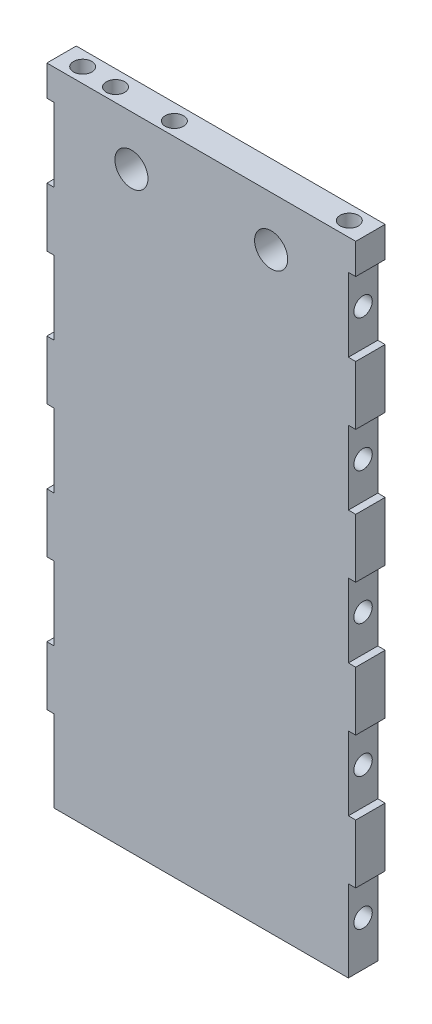
SolidWorks part; units mm, degrees
material "ABS"
ref_plane "前视基准面" through (0, 0, 0) normal (0, 0, 1) x (1, 0, 0)
ref_plane "上视基准面" through (0, 0, 0) normal (0, 1, 0) x (1, 0, 0)
ref_plane "右视基准面" through (0, 0, 0) normal (1, 0, 0) x (0, 0, -1)
sketch "草图1" plane through (0, 0, 0) normal (0, 0, 1) x (1, 0, 0)
  line L1 (42, -88.25) -> (-42, -88.25)
  line L2 (42, -88.25) -> (42, 88.25)
  line L3 (42, 88.25) -> (-42, 88.25)
  line L4 (-42, -88.25) -> (-42, 88.25)
  line L5 (42, -88.25) -> (-42, 88.25) construction
  line L6 (42, 88.25) -> (-42, -88.25) construction
  point P0 (0, 0)
  dimension "D1" = 176.5
  dimension "D2" = 84
extrude "凸台-拉伸1" add sketch "草图1" along normal mid plane 8
sketch "草图3" plane through (0, 0, -4) normal (0, 0, -1) x (-1, 0, 0)
  line L0 (42, 88.25) -> (42, -88.25) construction
  line L1 (32, 79.95) -> (-32, 79.95)
  line L2 (32, 79.95) -> (32, 86.25)
  line L3 (32, 86.25) -> (-32, 86.25)
  line L4 (-32, 79.95) -> (-32, 86.25)
  line L5 (-42, 88.25) -> (42, 88.25) construction
  line L6 (-42, -88.25) -> (-42, 88.25) construction
  dimension "D1" = 10
  dimension "D2" = 2
  dimension "D3" = 10
  dimension "D4" = 8.3
extrude "切除-拉伸1" [suppressed] cut sketch "草图3" against normal blind 10
ref_plane "基准面1" through (0, 91.25, 0) normal (0, 1, 0) x (1, 0, 0)
sketch "Sketch1" plane through (0, 0, 4) normal (0, 0, 1) x (1, 0, 0)
  line L0 (42, -88.25) -> (42, 88.25) construction
  line L1 (-42, 88.25) -> (42, 88.25)
  line L2 (-42, 88.25) -> (-42, 77.95)
  line L3 (-42, 77.95) -> (42, 77.95)
  line L4 (42, 88.25) -> (42, 77.95)
  dimension "D1" = 10.3
sketch "Sketch2" plane through (0, 0, 4) normal (0, 0, 1) x (1, 0, 0)
  line L0 (0, 0) -> (0, 60.2822) construction
  line L1 (-42, 77.95) -> (-40, 77.95)
  line L2 (-42, 77.95) -> (-42, 57.95)
  line L3 (-42, 57.95) -> (-40, 57.95)
  line L4 (-40, 77.95) -> (-40, 57.95)
  line L5 (-42, 41.95) -> (-40, 41.95)
  line L6 (-42, 41.95) -> (-42, 21.95)
  line L7 (-42, 21.95) -> (-40, 21.95)
  line L8 (-40, 41.95) -> (-40, 21.95)
  line L9 (-42, 5.95) -> (-40, 5.95)
  line L10 (-42, 5.95) -> (-42, -14.05)
  line L11 (-42, -14.05) -> (-40, -14.05)
  line L12 (-40, 5.95) -> (-40, -14.05)
  line L13 (-42, -30.05) -> (-40, -30.05)
  line L14 (-42, -30.05) -> (-42, -50.05)
  line L15 (-42, -50.05) -> (-40, -50.05)
  line L16 (-40, -30.05) -> (-40, -50.05)
  line L17 (-42, -66.05) -> (-40, -66.05)
  line L21 (-42, 77.95) -> (-42, 41.95) construction
  line L22 (42, 77.95) -> (42, 41.95) construction
  line L26 (42, -66.05) -> (40, -66.05)
  line L27 (40, -30.05) -> (40, -50.05)
  line L28 (42, -50.05) -> (40, -50.05)
  line L29 (42, -30.05) -> (42, -50.05)
  line L30 (42, -30.05) -> (40, -30.05)
  line L31 (40, 5.95) -> (40, -14.05)
  line L32 (42, -14.05) -> (40, -14.05)
  line L33 (42, 5.95) -> (42, -14.05)
  line L34 (42, 5.95) -> (40, 5.95)
  line L35 (40, 41.95) -> (40, 21.95)
  line L36 (42, 21.95) -> (40, 21.95)
  line L37 (42, 41.95) -> (42, 21.95)
  line L38 (42, 41.95) -> (40, 41.95)
  line L39 (40, 77.95) -> (40, 57.95)
  line L40 (42, 57.95) -> (40, 57.95)
  line L41 (42, 77.95) -> (42, 57.95)
  line L42 (42, 77.95) -> (40, 77.95)
  line L43 (-42, -86.05) -> (-40, -86.05) [skipped]
  line L44 (-40, -66.05) -> (-40, -86.05) [skipped]
  line L45 (-42, -66.05) -> (-42, -86.05) [skipped]
  line L46 (-42, -66.05) -> (-42, -88.25)
  line L47 (-42, -88.25) -> (-40, -88.25)
  line L48 (-42, -88.25) -> (42, -88.25) construction
  line L49 (-40, -88.25) -> (-40, -66.05)
  line L50 (40, -66.05) -> (40, -88.25)
  line L51 (40, -88.25) -> (42, -88.25)
  line L52 (42, -88.25) -> (42, -66.05)
  line L54 (-43, 86.25) -> (43, 86.25)
  line L55 (-43, 86.25) -> (-43, 88.25)
  line L56 (-43, 88.25) -> (43, 88.25)
  line L57 (43, 86.25) -> (43, 88.25)
  line L58 (-43, 86.25) -> (43, 88.25) construction
  line L59 (-43, 88.25) -> (43, 86.25) construction
  line L61 (-42, 88.25) -> (42, 88.25) construction
  line L62 (-42, 77.95) -> (42, 77.95) construction
  point P23 (0, 87.25)
  dimension "D1" = 20
  dimension "D2" = 2
  dimension "D4" = 36
  dimension "D5" = 86
  dimension "D6" = 2
  dimension "D3" = 5
extrude "Cut-Extrude1" cut sketch "Sketch2" against normal through all and the other way through all
sketch "Sketch3" plane through (40, 0, 0) normal (1, 0, 0) x (0, 0, -1)
  line L0 (0, 77.95) -> (0, 57.95) construction
  line L1 (4, 77.95) -> (-4, 77.95) construction
  line L2 (4, 57.95) -> (-4, 57.95) construction
  line L3 (0, 67.95) -> (0, 31.95) construction
  circle A0 centre (0, 67.95) radius 2.5
  circle A1 centre (0, 31.95) radius 2.5
  circle A2 centre (0, -4.05) radius 2.5
  circle A3 centre (0, -40.05) radius 2.5
  circle A4 centre (0, -76.05) radius 2.5
  dimension "D1" = 5
  dimension "D3" = 36
  dimension "D2" = 5
extrude "Cut-Extrude2" cut sketch "Sketch3" against normal blind 10
mirror "Mirror1" about plane through (0, 0, 0) normal (1, 0, 0) of "Cut-Extrude2"
sketch "Sketch4" plane through (0, -88.25, 0) normal (0, -1, 0) x (1, 0, 0)
  line L0 (0, 4) -> (0, -17.7794) construction
  line L1 (-40, 4) -> (40, 4) construction
  line L2 (0, 0) -> (-44.1169, 0) construction
  line L3 (-40, -4) -> (-40, 4) construction
  circle A0 centre (-34, 0) radius 2
  circle A1 centre (34, 0) radius 2
  circle A2 centre (0, 0) radius 2
  dimension "D1" = 4
  dimension "D3" = 4
  dimension "D2" = 6
extrude "Cut-Extrude3" cut sketch "Sketch4" against normal blind 8
sketch "Sketch5" plane through (0, 86.25, 0) normal (0, 1, 0) x (1, 0, 0)
  line L0 (-42, 4) -> (42, 4) construction
  line L2 (-42, -4) -> (-42, 4) construction
  line L4 (42, 4) -> (42, -4) construction
  circle A0 centre (-36.25, 0) radius 2.5
  circle A1 centre (36.25, 0) radius 2.5
  dimension "D3" = 5
  dimension "D6" = 5
  dimension "D7" = 5.75
  dimension "D2" = 5.75
  dimension "D1" = 4
  dimension "D5" = 4
extrude "Cut-Extrude4" cut sketch "Sketch5" against normal blind 10
sketch "Sketch6" plane through (0, 0, -4) normal (0, 0, -1) x (-1, 0, 0)
  line L0 (0, 0) -> (0, 49.5872) construction
  line L1 (42, 86.25) -> (-42, 86.25) construction
  line L2 (-42, 77.95) -> (-42, 86.25) construction
  circle A0 centre (-19, 72.75) radius 4.5
  circle A1 centre (19, 72.75) radius 4.5
  dimension "D1" = 9
  dimension "D4" = 23
  dimension "D2" = 13.5
extrude "Cut-Extrude5" cut sketch "Sketch6" against normal through all
sketch "Sketch7" plane through (0, 86.25, 0) normal (0, 1, 0) x (1, 0, 0)
  circle A0 centre (-11, -0.32) radius 1.5 construction
  circle A1 centre (-11, -0.32) radius 1.5 construction
  circle A2 centre (-11, -0.32) radius 2.5
  circle A3 centre (-27, -0.32) radius 1.5 construction
  circle A4 centre (-27, -0.32) radius 1.5 construction
  circle A5 centre (-27, -0.32) radius 2.5
  dimension "D1" = 5
  dimension "D2" = 5
extrude "Cut-Extrude6" cut sketch "Sketch7" against normal blind 10
